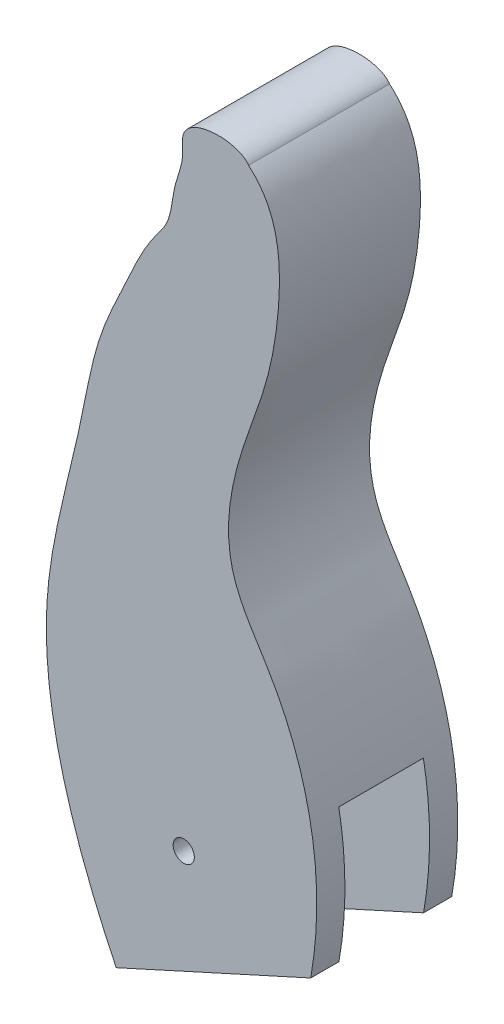
SolidWorks part; units mm, degrees
ref_plane "Спереди" through (0, 0, 0) normal (0, 0, 1) x (1, 0, 0)
ref_plane "Сверху" through (0, 0, 0) normal (0, 1, 0) x (1, 0, 0)
ref_plane "Справа" through (0, 0, 0) normal (1, 0, 0) x (0, 0, -1)
sketch "Sketch1" plane through (0, 0, 0) normal (0, 0, 1) x (1, 0, 0)
  line L0 (26.0375, -5.222) -> (-1.5517, -17.75)
  spline S0 degree 3 poles (17.2236, 90.1754) (21.4389, 86.628) (22.177, 76.5343) (19.9776, 64.3867) (15.2566, 52.8633) (12.8632, 39.7469) (25.7985, 22.513) (28.1614, 6.6563) (26.0375, -5.222) knots 0 0 0 0 0.157004 0.279495 0.373493 0.536349 0.644242 1 1 1 1
  spline S1 degree 3 poles (17.2236, 90.1754) (15.7918, 92.4001) (7.0975, 92.2631) (8.1827, 86.0993) (6.3819, 82.3941) (6.3689, 77.765) (2.6383, 73.3989) (-0.1225, 67.0307) (-4.5421, 58.1664) (-7.0544, 42.6173) (-15.0946, 17.1663) (-7.4441, -5.5846) (-1.5517, -17.75) knots 0 0 0 0 0.082765 0.103118 0.139065 0.183084 0.21057 0.276499 0.353941 0.452684 0.662009 1 1 1 1
extrude "Boss-Extrude1" add sketch "Sketch1" along normal blind 20
sketch "Sketch2" plane through (0, 0, 20) normal (0, 0, 1) x (1, 0, 0)
  line L0 (-20.6645, 13.7816) -> (39.1313, 13.7816)
  line L1 (39.1313, 13.7816) -> (36.3775, -18.6733)
  line L2 (36.3775, -18.6733) -> (-20.6645, -20.837)
  line L3 (-20.6645, -20.837) -> (-20.6645, 13.7816)
extrude "Cut-Extrude1" cut sketch "Sketch2" against normal blind 12 from offset 4 offset against normal yes
sketch "Sketch3" plane through (0, 0, 20) normal (0, 0, 1) x (1, 0, 0)
  circle A0 centre (8.0293, 1.3626) radius 1.5
  dimension "D1" = 3
extrude "Cut-Extrude2" cut sketch "Sketch3" against normal blind 36
